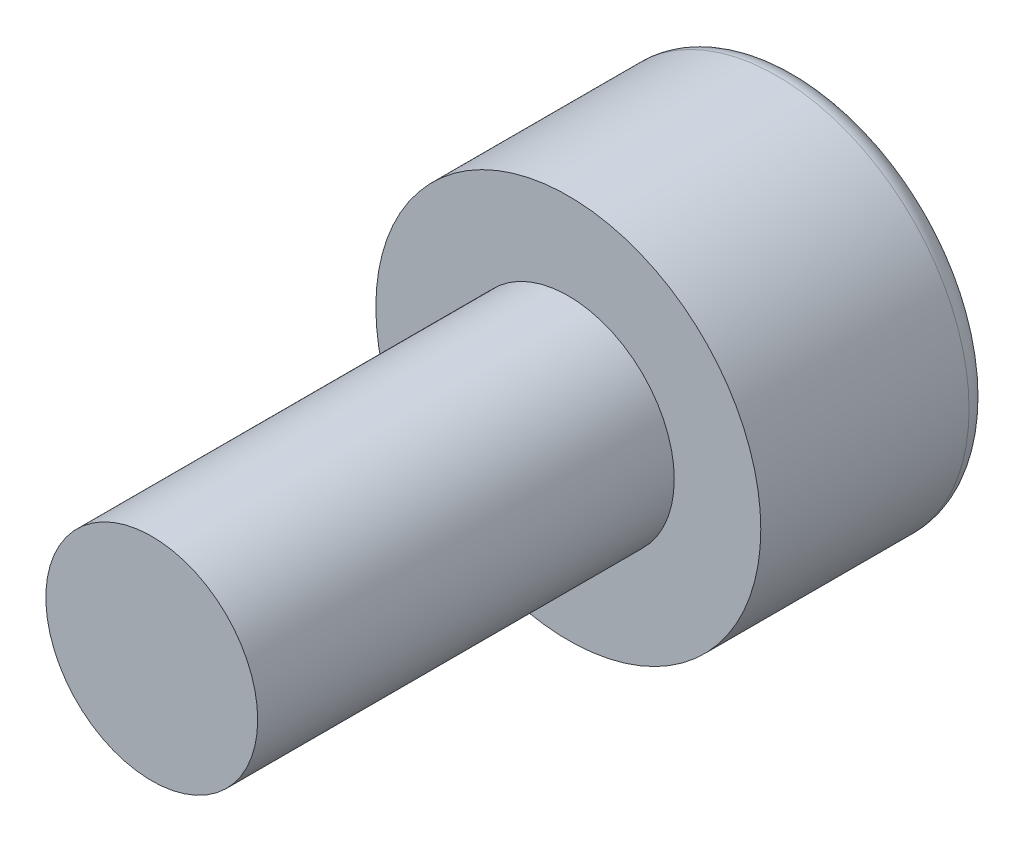
SolidWorks part; units mm, degrees
material "Acero aleado"
ref_plane "Alzado" through (0, 0, 0) normal (0, 0, 1) x (1, 0, 0)
ref_plane "Planta" through (0, 0, 0) normal (0, 1, 0) x (1, 0, 0)
ref_plane "Vista lateral" through (0, 0, 0) normal (1, 0, 0) x (0, 0, -1)
sketch "Croquis1" plane through (0, 0, 0) normal (0, 0, 1) x (1, 0, 0)
  circle A0 centre (0, 0) radius 1.475
  dimension "D1" = 2.95
extrude "Saliente-Extruir1" add sketch "Croquis1" along normal blind 5.8
sketch "Croquis2" plane through (0, 0, 0) normal (0, 0, -1) x (-1, 0, 0)
  circle A0 centre (0, 0) radius 2.68
  dimension "D1" = 5.36
extrude "Saliente-Extruir2" add sketch "Croquis2" along normal blind 3.2
sketch "Croquis3" plane through (0, 0, -3.2) normal (0, 0, -1) x (-1, 0, 0)
  line L1 (0, -1.7767) -> (1.5387, -0.8884)
  line L2 (1.5387, -0.8884) -> (1.5387, 0.8884)
  line L3 (1.5387, 0.8884) -> (0, 1.7767)
  line L4 (0, 1.7767) -> (-1.5387, 0.8884)
  line L5 (-1.5387, 0.8884) -> (-1.5387, -0.8884)
  line L6 (-1.5387, -0.8884) -> (0, -1.7767)
  circle A0 centre (0, 0) radius 1.5387 construction
extrude "Cortar-Extruir1" cut sketch "Croquis3" against normal blind 2.5
fillet "Redondeo1" radius 0.3 1 edges at (-2.68, 0, -3.2)
